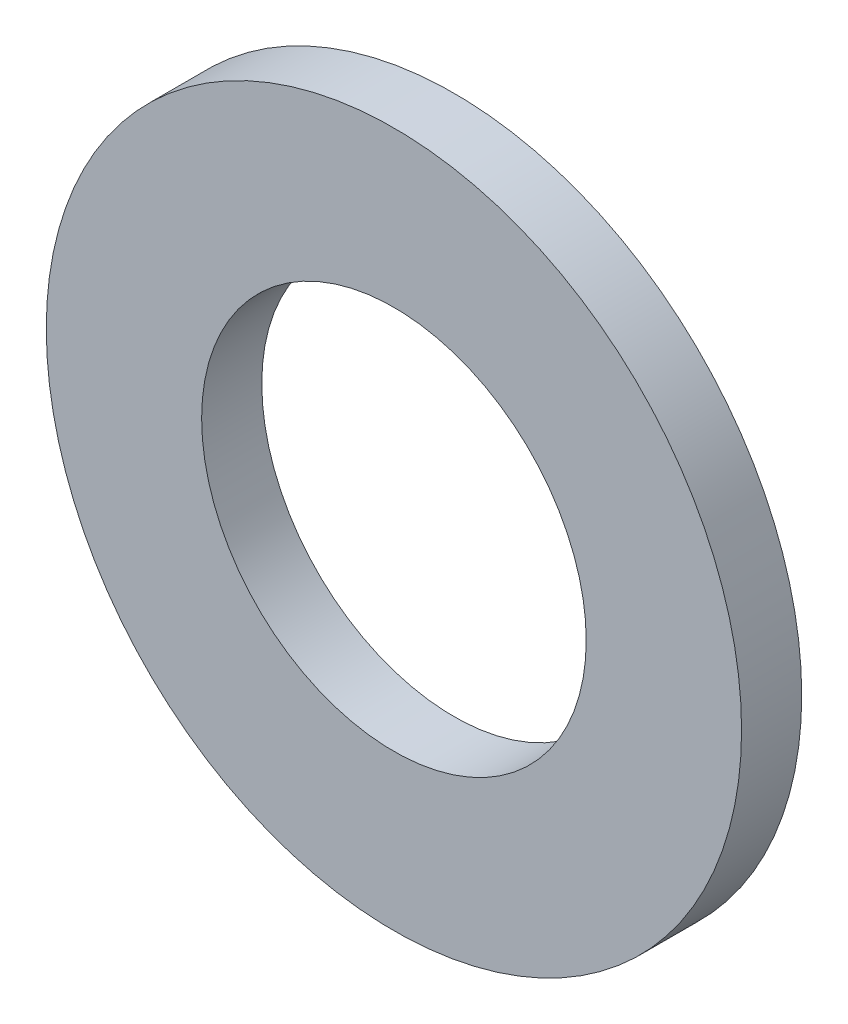
SolidWorks part; units mm, degrees
other "Imported1"
material "Plain Carbon Steel"
ref_plane "Front Plane" through (0, 0, 0) normal (0, 0, 1) x (1, 0, 0)
ref_plane "Top Plane" through (0, 0, 0) normal (0, 1, 0) x (1, 0, 0)
ref_plane "Right Plane" through (0, 0, 0) normal (1, 0, 0) x (0, 0, -1)
sketch "Sketch1" plane through (0, 0, 0) normal (0, 0, 1) x (1, 0, 0)
  line L0 (-9.3218, 0) -> (9.3218, 0) construction
  line L1 (-5.1562, 0) -> (5.1562, 0) construction
  circle A0 centre (0, 0) radius 5.1562 construction
  circle A1 centre (0, 0) radius 9.3218 construction
  point P8 (0, 0)
  point P9 (0, 9.3218)
  point P10 (0, -5.1562)
  point P11 (5.1562, 0)
  dimension "ID" = 10.3124
  dimension "OD" = 18.6436
sketch "Sketch2" plane through (0, 0, 0) normal (1, 0, 0) x (0, 0, -1)
  line L0 (-0.8064, 9.3218) -> (0.8065, 9.3218) construction
  point P2 (0, 9.3218)
  dimension "Thickness Range" = 1.6129
sketch "Sketch3" plane through (0, 0, 0) normal (0, 0, 1) x (1, 0, 0)
  circle A0 centre (0, 0) radius 5.1562
  circle A1 centre (0, 0) radius 9.3218
extrude "Boss-Extrude1" add sketch "Sketch3" along normal up to vertex (0.8065 mm away) and the other way up to vertex (0.8065 mm away) up to point (0, 9.3218, 0.8064) other way up to point (0, 9.3218, -0.8065)
